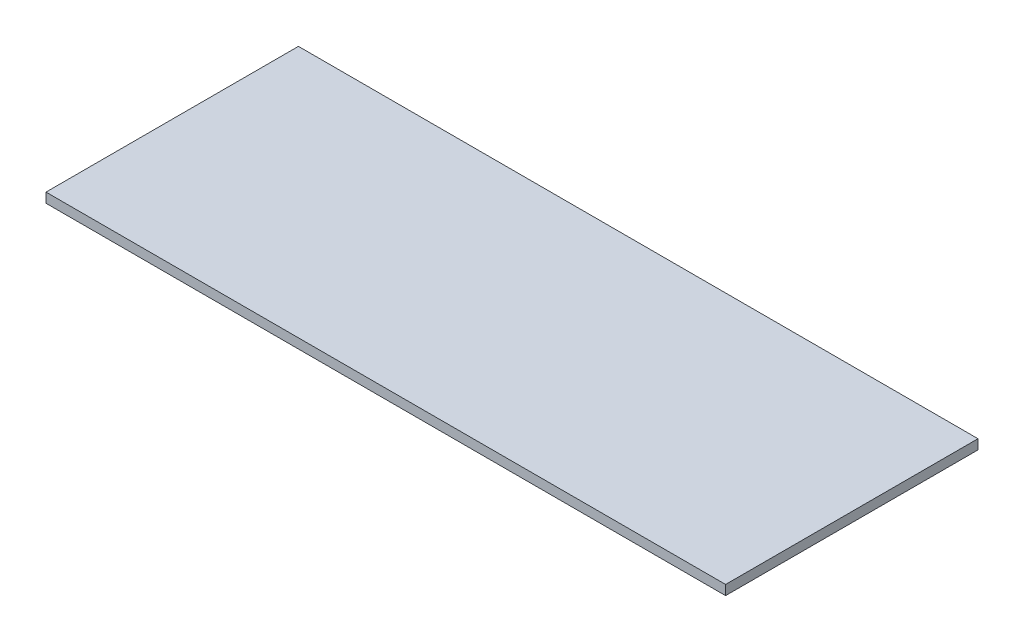
SolidWorks part; units mm, degrees
ref_plane "Front Plane" through (0, 0, 0) normal (0, 0, 1) x (1, 0, 0)
ref_plane "Top Plane" through (0, 0, 0) normal (0, 1, 0) x (1, 0, 0)
ref_plane "Right Plane" through (0, 0, 0) normal (1, 0, 0) x (0, 0, -1)
sketch "Sketch1" plane through (0, 0, 0) normal (0, 1, 0) x (1, 0, 0)
  line L1 (-175, 65) -> (175, 65)
  line L2 (-175, 65) -> (-175, -65)
  line L3 (-175, -65) -> (175, -65)
  line L4 (175, 65) -> (175, -65)
  line L5 (-175, 65) -> (175, -65) construction
  line L6 (-175, -65) -> (175, 65) construction
  point P0 (0, 0)
  dimension "D1" = 350
  dimension "D2" = 130
extrude "Boss-Extrude1" add sketch "Sketch1" along normal blind 5
